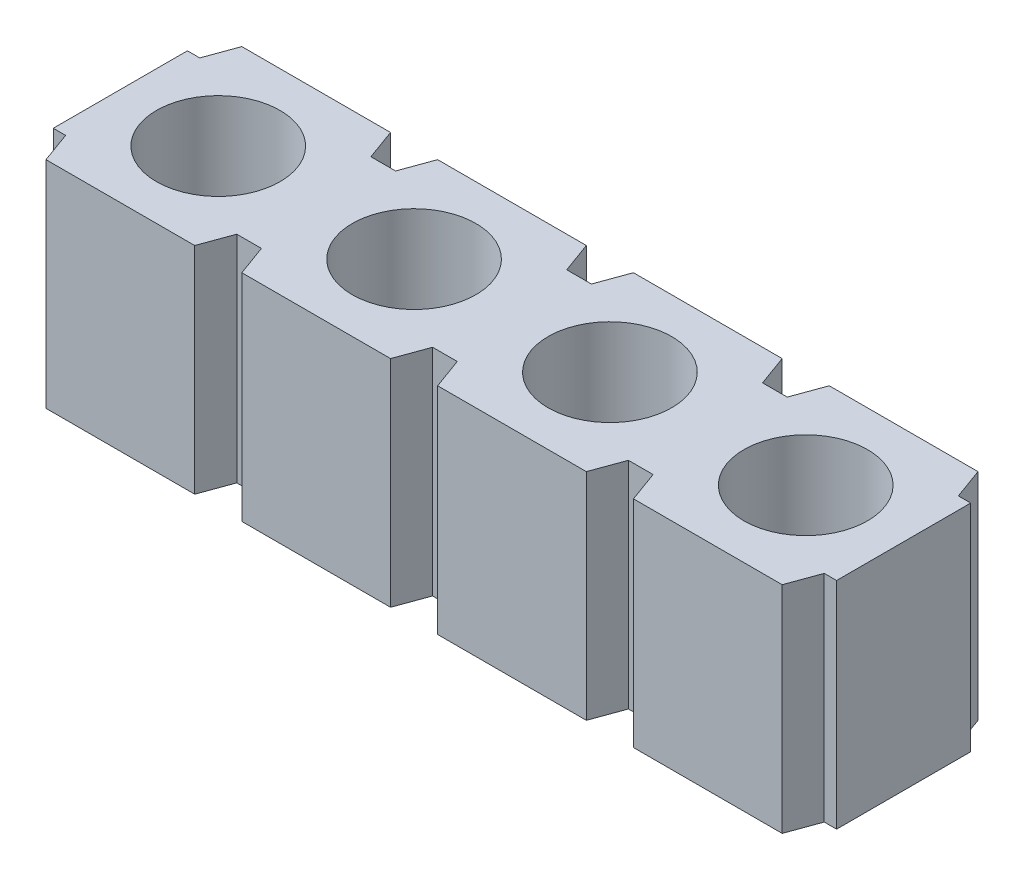
SolidWorks part; units mm, degrees
material "Nylon 46"
ref_plane "Front Plane" through (0, 0, 0) normal (0, 0, 1) x (1, 0, 0)
ref_plane "Top Plane" through (0, 0, 0) normal (0, 1, 0) x (1, 0, 0)
ref_plane "Right Plane" through (0, 0, 0) normal (1, 0, 0) x (0, 0, -1)
sketch "Sketch1" plane through (0, 0, 0) normal (0, 1, 0) x (1, 0, 0)
  line L0 (9.8544, 0.4) -> (9.6944, 0.4)
  line L1 (9.8544, 2.1399) -> (9.8544, 0.4)
  line L2 (-0.3056, 2.1399) -> (-0.1456, 2.1399)
  line L3 (-0.3056, 2.1399) -> (-0.3056, 0.4)
  line L4 (0, 0) -> (9.5487, 0)
  line L5 (0, 2.54) -> (-0.1456, 2.1399)
  line L6 (0, 0) -> (-0.1456, 0.4)
  line L7 (-0.3056, 0.4) -> (-0.1456, 0.4)
  line L9 (9.5487, 0) -> (9.6944, 0.4)
  line L10 (9.5487, 2.54) -> (9.6944, 2.1399)
  line L11 (9.8544, 2.1399) -> (9.6944, 2.1399)
  line L16 (9.5487, 2.54) -> (0, 2.54)
  dimension "D2" = 2.54
  dimension "D3" = 20
  dimension "D4" = 0.4
  dimension "D5" = 0.4
  dimension "D7" = 0.16
  dimension "INSLENGTH" = 10.16
extrude "Extrude1" add sketch "Sketch1" against normal blind 2.794
hole_wizard "Hole1" positions "3DSketch2" profile "Sketch3" legacy end condition through all
sketch3d "3DSketch2"
  line L2 (-0.3056, 0, -2.1399) -> (-0.3056, 0, -0.4) construction
  line L3 (9.5487, 0, -2.54) -> (0, 0, -2.54) construction
  point P0 (0.9644, 0, -1.27)
  dimension "D1" = 1.27
  dimension "D2" = 1.27
sketch "Sketch3" plane through (0.9644, 0, -1.27) normal (1, 0, 0) x (0, 0, 1)
  line L0 (0, 0) -> (0, 2.794)
  line L1 (0, 2.794) -> (0.8014, 2.794)
  line L2 (0.8014, 2.794) -> (0.8014, 0)
  line L3 (0.8014, 0) -> (0, 0)
  line L4 (0, 110) -> (0, -10) construction
  dimension "Diameter" = 1.6027
  dimension "Depth" = 2.794
sketch "Sketch4" plane through (0, 0, 0) normal (0, 1, 0) x (1, 0, 0)
  line L0 (1.9288, 0) -> (2.54, 0)
  line L2 (0, 0) -> (9.5487, 0) construction
  line L5 (2.0744, 0.4) -> (1.9288, 0)
  line L6 (2.3944, 0.4) -> (2.54, 0)
  line L7 (9.5487, 2.54) -> (0, 2.54) construction
  line L8 (2.0744, 0.4) -> (2.3944, 0.4)
  line L10 (2.0744, 2.1399) -> (2.3944, 2.1399)
  line L11 (2.3944, 2.1399) -> (2.54, 2.54)
  line L12 (2.0744, 2.1399) -> (1.9288, 2.54)
  line L13 (1.9288, 2.54) -> (2.54, 2.54)
  line L17 (-0.3056, 2.1399) -> (-0.3056, 0.4) construction
  dimension "D1" = 0.4
  dimension "D2" = 0.32
  dimension "D3" = 70
  dimension "D4" = 0.6112
  dimension "D5" = 0.4001
  dimension "D6" = 2.2344
extrude "Extrude2" cut sketch "Sketch4" against normal blind 2.794
pattern_linear "LPattern1" count 4 spacing 2.54 along (1, 0, 0) of "Hole1"
pattern_linear "LPattern2" count 63 spacing 2.54 along (1, 0, 0) of "Extrude2"
